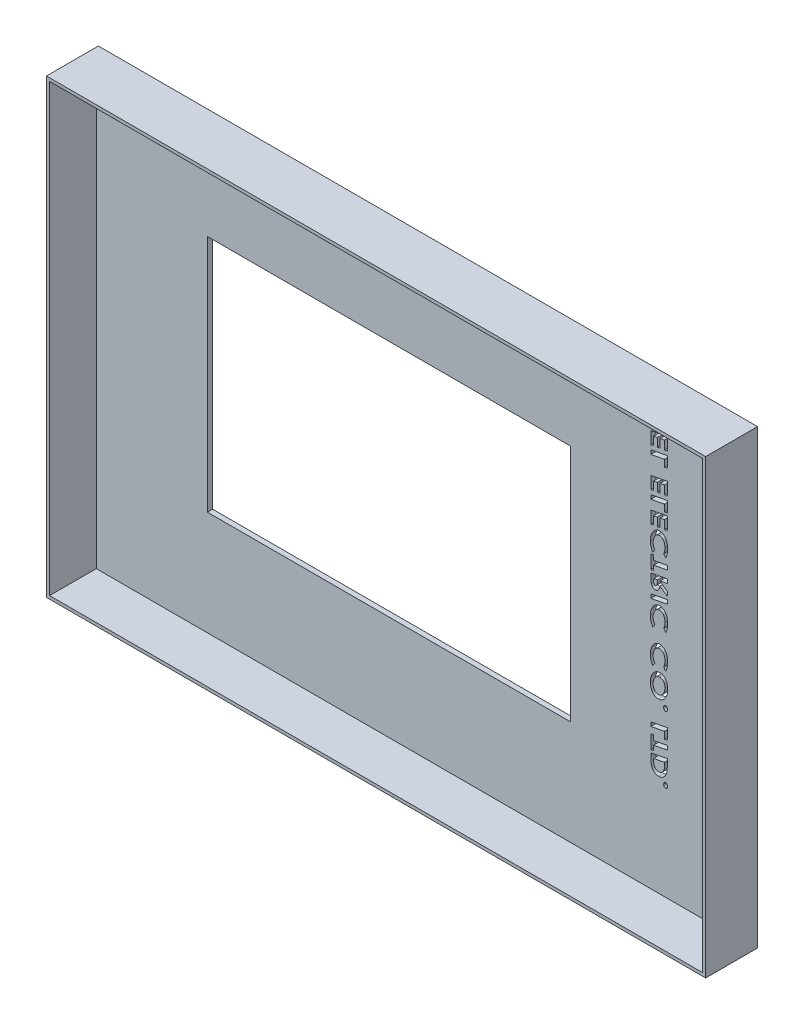
SolidWorks part; units mm, degrees
ref_plane "Front Plane" through (0, 0, 0) normal (0, 0, 1) x (1, 0, 0)
ref_plane "Top Plane" through (0, 0, 0) normal (0, 1, 0) x (1, 0, 0)
ref_plane "Right Plane" through (0, 0, 0) normal (1, 0, 0) x (0, 0, -1)
sketch "Sketch1" plane through (0, 0, 0) normal (0, 0, 1) x (1, 0, 0)
  line L1 (-48.3488, 34.8381) -> (78.6512, 34.8381)
  line L2 (-48.3488, 34.8381) -> (-48.3488, -52.1619)
  line L3 (-48.3488, -52.1619) -> (78.6512, -52.1619)
  line L4 (78.6512, 34.8381) -> (78.6512, -52.1619)
  line L5 (-26.3488, 13.5656) -> (43.6512, 13.5656)
  line L6 (-26.3488, 13.5656) -> (-26.3488, -31.4344)
  line L7 (-26.3488, -31.4344) -> (43.6512, -31.4344)
  line L8 (43.6512, 13.5656) -> (43.6512, -31.4344)
  dimension "D1" = 127
  dimension "D2" = 87
  dimension "D5" = 22
extrude "Boss-Extrude1" add sketch "Sketch1" along normal blind 10
sketch "Sketch2" plane through (0, 0, 10) normal (0, 0, 1) x (1, 0, 0)
  line L1 (-47.7488, 34.2381) -> (78.0512, 34.2381)
  line L2 (-47.7488, 34.2381) -> (-47.7488, -51.5619)
  line L3 (-47.7488, -51.5619) -> (78.0512, -51.5619)
  line L4 (78.0512, 34.2381) -> (78.0512, -51.5619)
  line L5 (-48.3488, 34.8381) -> (-48.3488, -52.1619) construction
  dimension "D1" = 125.8
  dimension "D2" = 85.8
  dimension "D4" = 0.6
extrude "Cut-Extrude1" cut sketch "Sketch2" against normal blind 9 contours L2 L1 L4 L3
sketch "Sketch3" plane through (0, 0, 0) normal (0, 0, -1) x (-1, 0, 0)
  line L0 (-78.6512, -52.1619) -> (-78.6512, 34.8381) construction
  line L1 (-43.6512, 14.5614) -> (26.3488, 14.5614)
  line L2 (-43.6512, 14.5614) -> (-43.6512, -30.4386)
  line L3 (-43.6512, -30.4386) -> (26.3488, -30.4386)
  line L4 (26.3488, 14.5614) -> (26.3488, -30.4386)
  text T0 "<b><i>PIXEL ELECTRIC CO. LTD.</i></b>" font "Century Gothic" height 3.175
  dimension "D1" = 70
  dimension "D2" = 35
  dimension "D3" = 45
extrude "Cut-Extrude2" cut sketch "Sketch3" against normal blind 9
